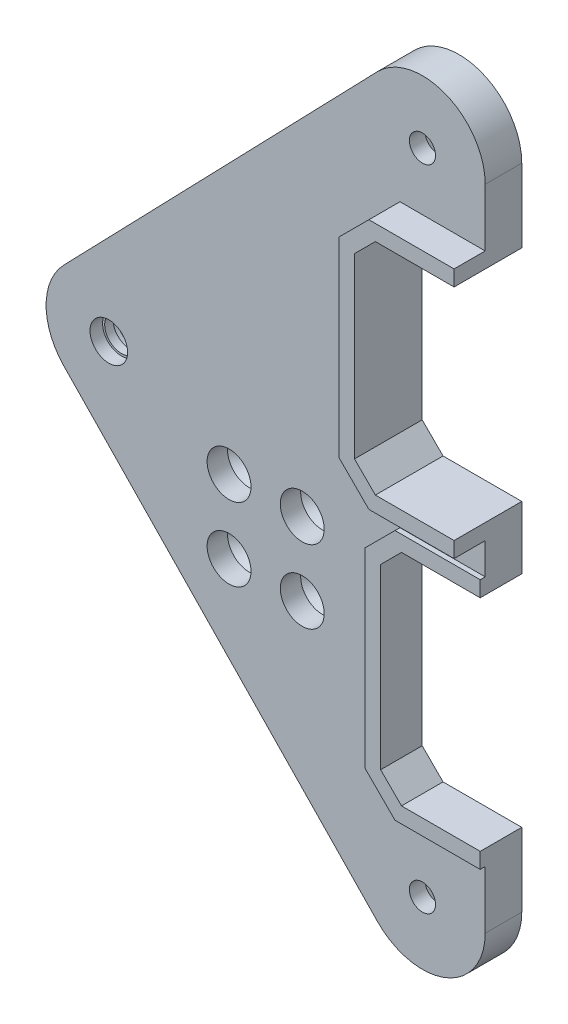
SolidWorks part; units mm, degrees
ref_plane "Front Plane" through (0, 0, 0) normal (0, 0, 1) x (1, 0, 0)
ref_plane "Top Plane" through (0, 0, 0) normal (0, 1, 0) x (1, 0, 0)
ref_plane "Right Plane" through (0, 0, 0) normal (1, 0, 0) x (0, 0, -1)
sketch "Sketch1" plane through (0, 0, 0) normal (0, 0, 1) x (1, 0, 0)
  line L0 (-8.6266, 70.3916) -> (-68.6266, 8.3416)
  line L1 (-68.6266, -8.3416) -> (-8.6266, -70.3916)
  line L2 (12, -62.05) -> (12, 62.05)
  line L3 (0, 0) -> (-60, 0) construction
  arc A0 (-68.6266, 8.3416) -> (-68.6266, -8.3416) centre (-60, 0) ccw
  arc A1 (-8.6266, -70.3916) -> (12, -62.05) centre (0, -62.05) ccw
  arc A2 (12, 62.05) -> (-8.6266, 70.3916) centre (0, 62.05) ccw
  dimension "D1" = 12
extrude "Boss-Extrude1" add sketch "Sketch1" along normal blind 7
sketch "Sketch3" plane through (0, 0, 7) normal (0, 0, -1) x (-1, 0, 0)
  line L12 (-12, 3) -> (-12, 51)
  line L13 (-12, -62.05) -> (-12, 62.05) construction
  line L24 (4.2996, 3) -> (10.05, 8.7504)
  line L25 (10.05, 8.7504) -> (10.05, 45.2496)
  line L26 (10.05, 45.2496) -> (4.2996, 51)
  line L27 (4.2996, 51) -> (-32.1996, 51)
  line L28 (-32.1996, 51) -> (-37.95, 45.2496)
  line L29 (-37.95, 45.2496) -> (-37.95, 38.5)
  line L30 (-37.95, 38.5) -> (-46.65, 38.5)
  line L31 (-46.65, 38.5) -> (-46.65, 15.5)
  line L32 (-46.65, 15.5) -> (-37.95, 15.5)
  line L33 (-37.95, 15.5) -> (-37.95, 8.7504)
  line L34 (-37.95, 8.7504) -> (-32.1996, 3)
  line L35 (-32.1996, 3) -> (4.2996, 3)
  line L36 (4.2996, 3) -> (10.05, 8.7504)
  line L37 (10.05, 8.7504) -> (10.05, 45.2496)
  line L38 (10.05, 45.2496) -> (4.2996, 51)
  line L39 (4.2996, 51) -> (-12, 51)
  line L47 (-12, 3) -> (4.2996, 3)
  dimension "D1" = 3
extrude "Boss-Extrude2" add sketch "Sketch3" against normal up to surface (5.95 mm away)
sketch "Sketch4" plane through (0, 0, 7) normal (0, 0, 1) x (1, 0, 0)
  line L12 (12, -51) -> (12, -3)
  line L13 (12, -62.05) -> (12, 62.05) construction
  line L24 (-10.05, -45.2496) -> (-4.2996, -51)
  line L25 (-10.05, -8.7504) -> (-10.05, -45.2496)
  line L26 (-4.2996, -3) -> (-10.05, -8.7504)
  line L27 (32.1996, -3) -> (-4.2996, -3)
  line L28 (37.95, -8.7504) -> (32.1996, -3)
  line L29 (37.95, -15.5) -> (37.95, -8.7504)
  line L30 (46.65, -15.5) -> (37.95, -15.5)
  line L31 (46.65, -38.5) -> (46.65, -15.5)
  line L32 (37.95, -38.5) -> (46.65, -38.5)
  line L33 (37.95, -45.2496) -> (37.95, -38.5)
  line L34 (32.1996, -51) -> (37.95, -45.2496)
  line L35 (-4.2996, -51) -> (32.1996, -51)
  line L36 (-10.05, -45.2496) -> (-4.2996, -51)
  line L37 (-10.05, -8.7504) -> (-10.05, -45.2496)
  line L38 (-4.2996, -3) -> (-10.05, -8.7504)
  line L39 (12, -3) -> (-4.2996, -3)
  line L47 (-4.2996, -51) -> (12, -51)
  dimension "D1" = 3
extrude "Boss-Extrude3" add sketch "Sketch4" along normal up to surface (0.95 mm away)
sketch "Sketch2" plane through (0, 0, 0) normal (0, 0, -1) x (-1, 0, 0)
  line L0 (-30.957, 48) -> (3.057, 48) construction
  line L1 (3.057, 48) -> (7.05, 44.007) construction
  line L2 (7.05, -9.993) -> (7.05, -44.007) construction
  line L3 (7.05, -44.007) -> (3.057, -48) construction
  line L4 (3.057, -48) -> (-30.957, -48) construction
  line L5 (-34.95, 48) -> (3.057, 48)
  line L6 (3.057, 48) -> (7.05, 44.007)
  line L7 (7.05, 44.007) -> (7.05, 9.993)
  line L8 (7.05, -44.007) -> (3.057, -48)
  line L9 (3.057, -48) -> (-34.95, -48)
  line L10 (-34.95, -48) -> (-34.95, 48)
  line L11 (-34.95, 9.993) -> (-34.95, 18.5) construction
  line L12 (3.057, 6) -> (-30.957, 6) construction
  line L13 (7.05, 9.993) -> (3.057, 6) construction
  line L14 (-30.957, -6) -> (3.057, -6) construction
  line L15 (3.057, -6) -> (7.05, -9.993) construction
  line L16 (3.057, 6) -> (-30.957, 6)
  line L17 (7.05, 9.993) -> (3.057, 6)
  line L18 (-30.957, -6) -> (3.057, -6)
  line L19 (3.057, -6) -> (7.05, -9.993)
  line L20 (-30.957, 6) -> (-30.957, -6)
  line L21 (7.05, -9.993) -> (7.05, -44.007)
extrude "Cut-Extrude1" cut sketch "Sketch2" against normal through all
sketch "Sketch5" plane through (0, 0, 7) normal (0, 0, 1) x (1, 0, 0)
  circle A0 centre (-60, 0) radius 3.6
  dimension "D1" = 7.2
extrude "Cut-Extrude2" cut sketch "Sketch5" against normal up to surface (2.4 mm away)
sketch "Sketch6" plane through (0, 0, 0) normal (0, 0, -1) x (-1, 0, 0)
  point P0 (60, 0)
hole_wizard "CBORE for M5 SHCS1" positions "Sketch6" profile "Sketch7" counterbore size "M5" standard "ANSI Metric" end condition through all
sketch "Sketch7" plane through (-60, 0, 0) normal (1, 0, 0) x (0, 1, 0)
  line L0 (0, 0) -> (0, 12.95)
  line L1 (0, 12.95) -> (3.2, 12.95)
  line L3 (3.2, 12.95) -> (3.2, 3)
  line L4 (3.2, 3) -> (6.4, 3)
  line L5 (6.4, 3) -> (6.4, 0)
  line L7 (6.4, 0) -> (0, 0)
  line L11 (0, -6.35) -> (0, 107.95) construction
  dimension "Thru Hole Dia." = 6.4
  dimension "Thru Hole Depth" = 12.95
  dimension "C'Bore Dia." = 12.8
  dimension "C'Bore Depth" = 3
sketch "Sketch8" plane through (0, 0, 0) normal (0, 0, -1) x (-1, 0, 0)
  line L1 (-2.3094, 58.05) -> (2.3094, 58.05)
  line L2 (2.3094, 58.05) -> (4.6188, 62.05)
  line L3 (4.6188, 62.05) -> (2.3094, 66.05)
  line L4 (2.3094, 66.05) -> (-2.3094, 66.05)
  line L5 (-2.3094, 66.05) -> (-4.6188, 62.05)
  line L6 (-4.6188, 62.05) -> (-2.3094, 58.05)
  circle A0 centre (0, 62.05) radius 4 construction
  dimension "D1" = 8
extrude "Cut-Extrude3" cut sketch "Sketch8" against normal blind 4
sketch "Sketch9" plane through (0, 0, 4) normal (0, 0, -1) x (-1, 0, 0)
  point P0 (0, 62.05)
hole_wizard "Ø5.0 (5) Diameter Hole1" positions "Sketch9" profile "Sketch10" hole size "Ø5.0" standard "ANSI Metric" end condition through all
sketch "Sketch10" plane through (0, 62.05, 4) normal (1, 0, 0) x (0, 1, 0)
  line L0 (0, 0) -> (0, 8.95)
  line L1 (0, 8.95) -> (2.5, 8.95)
  line L2 (2.5, 8.95) -> (2.5, 0)
  line L5 (2.5, 0) -> (0, 0)
  line L11 (0, -6.35) -> (0, 107.95) construction
  dimension "Thru Hole Dia." = 5
  dimension "Thru Hole Depth" = 8.95
mirror "Mirror1" about plane through (0, 0, 0) normal (0, 1, 0) of "Ø5.0 (5) Diameter Hole1", "Cut-Extrude3"
sketch "Sketch11" plane through (0, 0, 7) normal (0, 0, -1) x (-1, 0, 0)
  point P0 (37, -24.5)
  point P1 (23, -24.5)
  point P2 (23, -10.5)
  point P3 (37, -10.5)
hole_wizard "CSK for M4 SFHCS1" positions "Sketch11" profile "Sketch12" countersink size "M4" standard "ANSI Metric" end condition through all
sketch "Sketch12" plane through (-37, -24.5, 7) normal (1, 0, 0) x (0, -1, 0)
  line L0 (0, 0) -> (0, 7)
  line L1 (0, 7) -> (2.1, 7)
  line L2 (2.1, 7) -> (2.1, 6)
  line L3 (2.1, 6) -> (4.2, 3.9)
  line L4 (4.2, 3.9) -> (4.2, 0)
  line L6 (4.2, 0) -> (0, 0)
  line L7 (-2.1, 6) -> (-4.2, 3.9) construction
  line L11 (0, -6.35) -> (0, 107.95) construction
  dimension "Thru Hole Dia." = 4.2
  dimension "Thru Hole Depth" = 7
  dimension "C'Sink Dia." = 8.4
  dimension "C'Sink Angle" = 90
  dimension "Head Clearance" = 3.9
